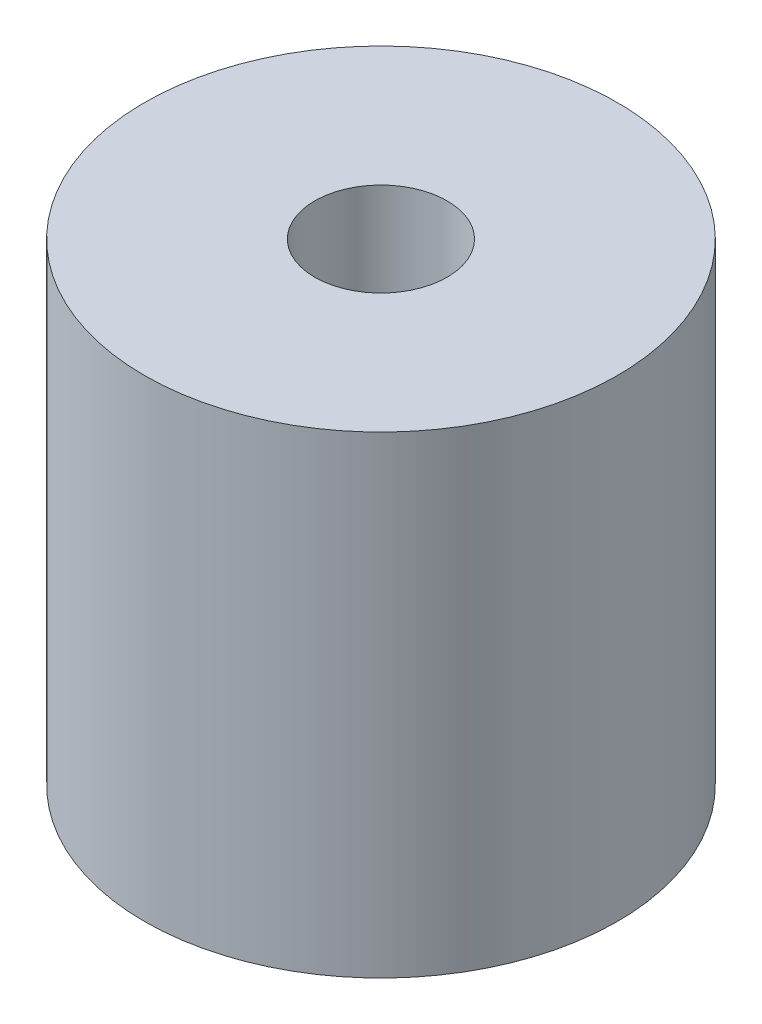
SolidWorks part; units mm, degrees
ref_plane "Front Plane" through (0, 0, 0) normal (0, 0, 1) x (1, 0, 0)
ref_plane "Top Plane" through (0, 0, 0) normal (0, 1, 0) x (1, 0, 0)
ref_plane "Right Plane" through (0, 0, 0) normal (1, 0, 0) x (0, 0, -1)
sketch "Sketch1" plane through (0, 0, 0) normal (0, 1, 0) x (1, 0, 0)
  circle A0 centre (0, 0) radius 0.889
  circle A1 centre (0, 0) radius 3.175
  dimension "D1" = 1.778
  dimension "D2" = 6.35
extrude "Boss-Extrude1" add sketch "Sketch1" along normal blind 6.35
